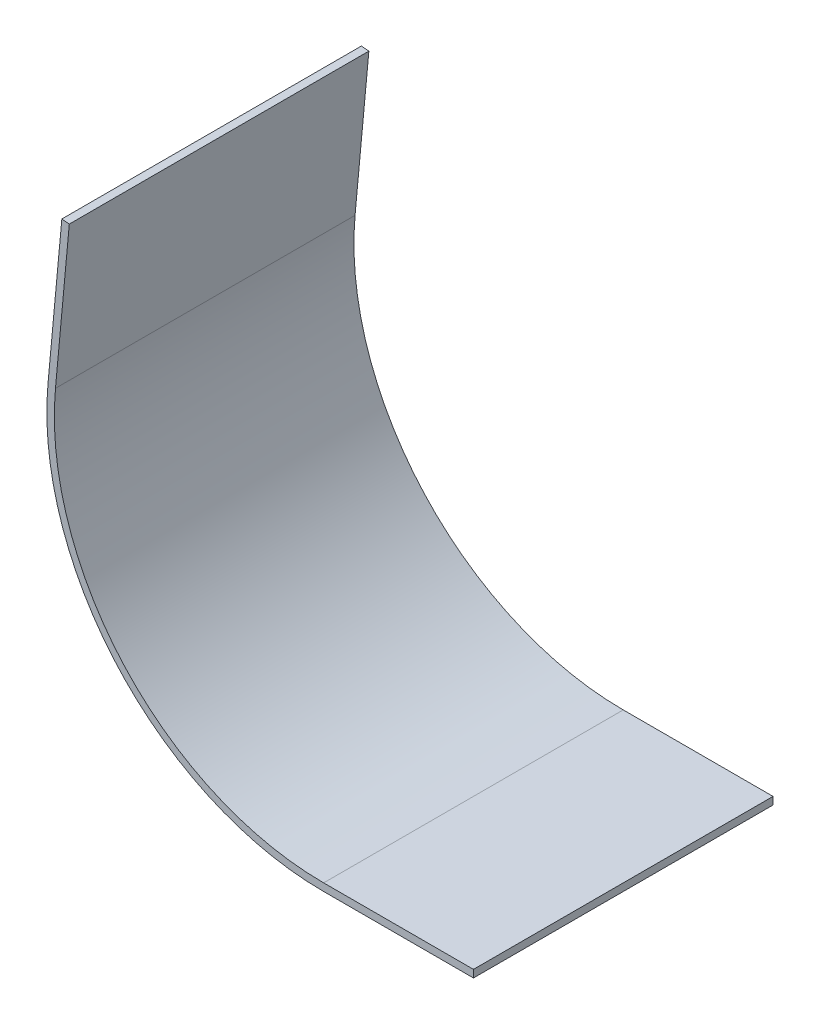
SolidWorks part; units mm, degrees
ref_plane "Front Plane" through (0, 0, 0) normal (0, 0, 1) x (1, 0, 0)
ref_plane "Top Plane" through (0, 0, 0) normal (0, 1, 0) x (1, 0, 0)
ref_plane "Right Plane" through (0, 0, 0) normal (1, 0, 0) x (0, 0, -1)
sketch "Sketch1" plane through (0, 0, 0) normal (0, 0, 1) x (1, 0, 0)
  line L0 (10, -0.25) -> (10, 0.25)
  line L1 (10, -0.25) -> (0, -0.25)
  line L2 (10, 0.25) -> (0, 0.25)
  line L4 (-17.4803, 29.895) -> (-16.9824, 29.8489)
  line L5 (-17.4803, 29.895) -> (-18.4031, 19.9377)
  line L6 (-16.9824, 29.8489) -> (-17.9053, 19.8916)
  line L8 (0, 5) -> (0, 0.25) construction
  line L9 (0, -0.25) -> (0, -5) construction
  arc A0 (0, 0.25) -> (-17.9053, 19.8916) centre (0, 18.232) cw
  arc A1 (-18.4031, 19.9377) -> (0, -0.25) centre (0, 18.232) ccw
  point P14 (0, 0.25)
  point P17 (0, -0.25)
extrude "Boss-Extrude1" add sketch "Sketch1" against normal blind 20
